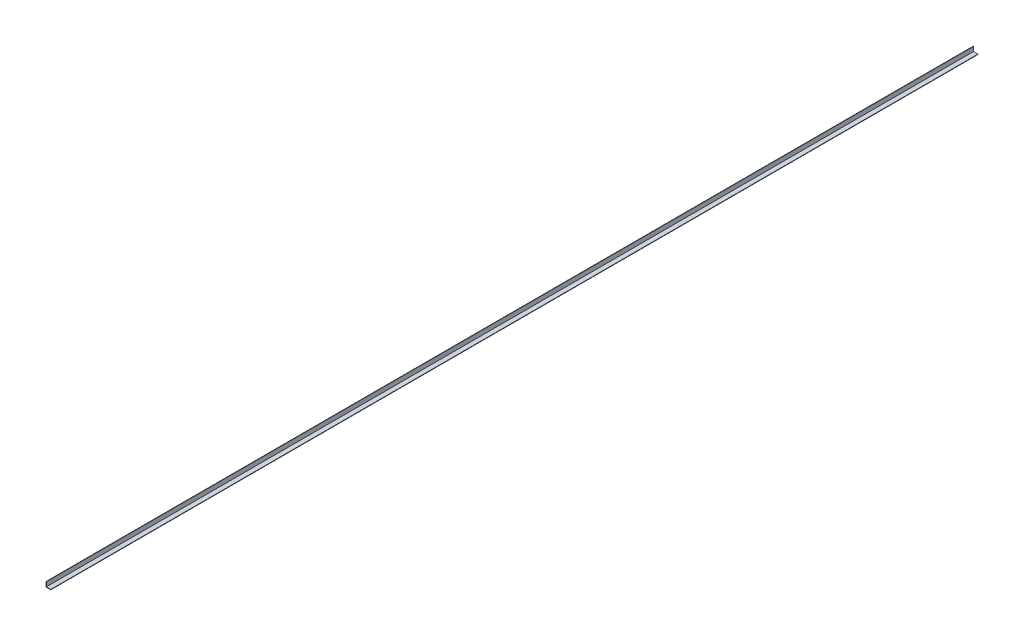
SolidWorks part; units mm, degrees
material "ASTM A36 Acero"
ref_plane "Alzado" through (0, 0, 0) normal (0, 0, 1) x (1, 0, 0)
ref_plane "Planta" through (0, 0, 0) normal (0, 1, 0) x (1, 0, 0)
ref_plane "Vista lateral" through (0, 0, 0) normal (1, 0, 0) x (0, 0, -1)
sketch "Croquis1" plane through (0, 0, 0) normal (0, 0, 1) x (1, 0, 0)
  line L0 (0, 31.75) -> (0, 0)
  line L1 (0, 0) -> (31.75, 0)
  line L2 (31.75, 0) -> (31.75, 2.7)
  line L3 (31.75, 2.7) -> (2.7, 2.7)
  line L4 (2.7, 2.7) -> (2.7, 31.75)
  line L5 (2.7, 31.75) -> (0, 31.75)
  dimension "D1" = 2.7
  dimension "D2" = 31.75
extrude "Saliente-Extruir1" add sketch "Croquis1" against normal blind 6100
